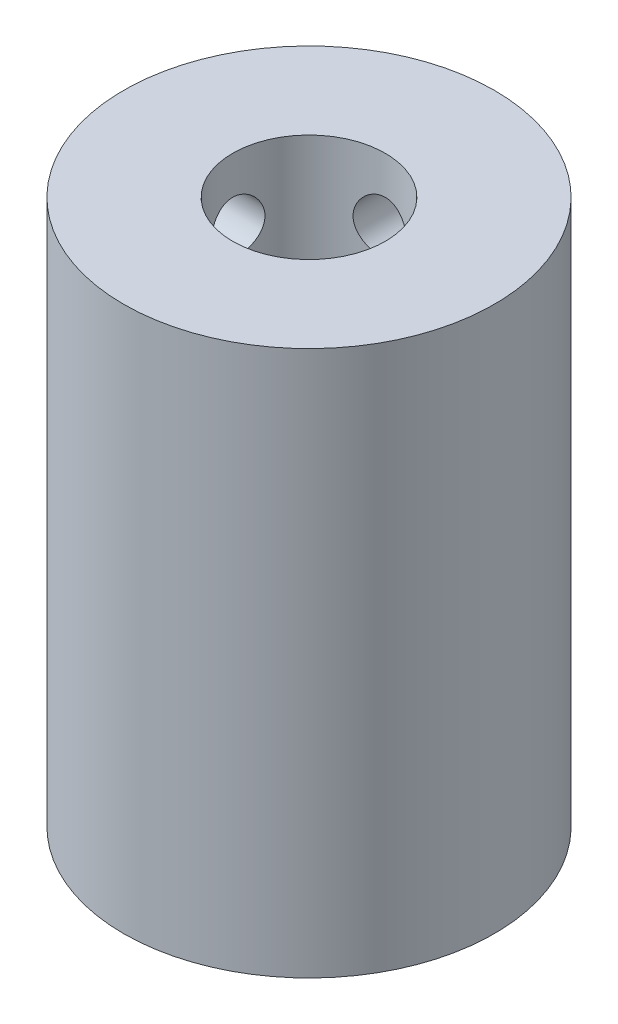
SolidWorks part; units mm, degrees
ref_plane "Front Plane" through (0, 0, 0) normal (0, 0, 1) x (1, 0, 0)
ref_plane "Top Plane" through (0, 0, 0) normal (0, 1, 0) x (1, 0, 0)
ref_plane "Right Plane" through (0, 0, 0) normal (1, 0, 0) x (0, 0, -1)
sketch "Sketch1" plane through (0, 0, 0) normal (0, 1, 0) x (1, 0, 0)
  circle A0 centre (0, 0) radius 7
  circle A1 centre (0, 0) radius 17
  dimension "D1" = 14
  dimension "D2" = 34
extrude "Boss-Extrude1" add sketch "Sketch1" along normal blind 50
sketch "Sketch2" plane through (0, 0, 0) normal (0, 0, 1) x (1, 0, 0)
  line L0 (17, 50) -> (-17, 50) construction
  line L1 (-17, 0) -> (17, 0) construction
  circle A0 centre (0, 44) radius 2.5
  circle A1 centre (0, 6) radius 2.5
  dimension "D1" = 5
  dimension "D2" = 5
  dimension "D3" = 6
  dimension "D4" = 6
extrude "Cut-Extrude1" cut sketch "Sketch2" against normal through all
sketch "Sketch3" plane through (0, 0, 0) normal (1, 0, 0) x (0, 0, -1)
  line L0 (17, 50) -> (-17, 50) construction
  circle A0 centre (0, 44) radius 2.5
  circle A1 centre (0, 6) radius 2.5
  dimension "D1" = 5
  dimension "D2" = 5
  dimension "D3" = 6
  dimension "D4" = 6
extrude "Cut-Extrude2" cut sketch "Sketch3" against normal through all
